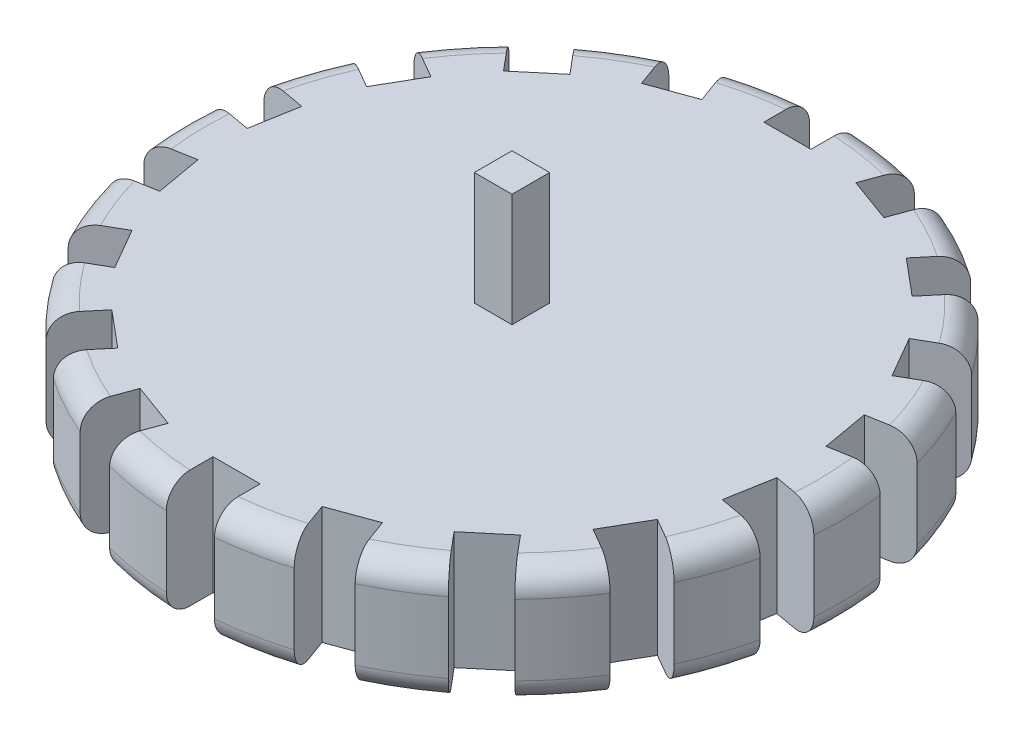
SolidWorks part; units mm, degrees
ref_plane "前视基准面" through (0, 0, 0) normal (0, 0, 1) x (1, 0, 0)
ref_plane "上视基准面" through (0, 0, 0) normal (0, 1, 0) x (1, 0, 0)
ref_plane "右视基准面" through (0, 0, 0) normal (1, 0, 0) x (0, 0, -1)
sketch "草图1" plane through (0, 0, 0) normal (0, 1, 0) x (1, 0, 0)
  line L1 (-27.9247, -7.2133) -> (-28.9247, -7.2133)
  line L2 (-27.9247, -7.2133) -> (-27.9247, -5.2133)
  line L3 (-27.9247, -5.2133) -> (-28.9247, -5.2133)
  line L4 (-28.9247, -7.2133) -> (-28.9247, -5.2133)
  circle A0 centre (-28.5698, 1.7867) radius 7
  dimension "D1" = 14
  dimension "D2" = 1
  dimension "D3" = 2
  dimension "D4" = 7
extrude "凸台-拉伸1" add sketch "草图1" along normal blind 2.5 contours A0
sketch "草图2" plane through (0, 2.5, 0) normal (0, 1, 0) x (1, 0, 0)
  line L1 (-28.9698, 2.1867) -> (-28.1698, 2.1867)
  line L2 (-28.9698, 2.1867) -> (-28.9698, 1.3867)
  line L3 (-28.9698, 1.3867) -> (-28.1698, 1.3867)
  line L4 (-28.1698, 2.1867) -> (-28.1698, 1.3867)
  line L5 (-28.9698, 2.1867) -> (-28.1698, 1.3867) construction
  line L6 (-28.9698, 1.3867) -> (-28.1698, 2.1867) construction
  point P0 (-28.5698, 1.7867)
extrude "凸台-拉伸2" add sketch "草图2" along normal blind 2.4
sketch "草图3" plane through (0, 0, 0) normal (0, -1, 0) x (1, 0, 0)
  circle A0 centre (-28.5698, -1.7867) radius 1
extrude "凸台-拉伸3" add sketch "草图3" along normal blind 1
fillet "圆角2" radius 0.5 2 edges at (-28.5698, 0, 5.2133) (-28.5698, 2.5, 5.2133)
sketch "草图4" plane through (0, 2.5, 0) normal (0, 1, 0) x (1, 0, 0)
  line L0 (-22.0698, 1.7867) -> (-35.0698, 1.7867) construction
  line L1 (-28.9177, -4.2133) -> (-27.9177, -4.2133)
  line L2 (-28.9177, -4.2133) -> (-28.9177, -6.2133)
  line L3 (-28.9177, -6.2133) -> (-27.9177, -6.2133)
  line L4 (-27.9177, -4.2133) -> (-27.9177, -6.2133)
  line L5 (-35.0698, 1.7867) -> (-28.5698, 8.2867) construction
  line L6 (-28.5698, 8.2867) -> (-28.5698, -4.7133) construction
  line L7 (-30.9489, -3.7325) -> (-31.6329, -5.6118)
  line L8 (-30.9489, -3.7325) -> (-30.0092, -4.0745)
  line L9 (-30.0092, -4.0745) -> (-30.6932, -5.9539)
  line L10 (-31.6329, -5.6118) -> (-30.6932, -5.9539)
  line L11 (-32.6931, -2.5859) -> (-33.9786, -4.118)
  line L12 (-32.6931, -2.5859) -> (-31.927, -3.2287)
  line L13 (-31.927, -3.2287) -> (-33.2126, -4.7608)
  line L14 (-33.9786, -4.118) -> (-33.2126, -4.7608)
  line L15 (-33.9399, -0.912) -> (-35.672, -1.912)
  line L16 (-33.9399, -0.912) -> (-33.4399, -1.778)
  line L17 (-33.4399, -1.778) -> (-35.172, -2.778)
  line L18 (-35.672, -1.912) -> (-35.172, -2.778)
  line L19 (-34.5391, 1.0874) -> (-36.5087, 0.7401)
  line L20 (-34.5391, 1.0874) -> (-34.3654, 0.1026)
  line L21 (-34.3654, 0.1026) -> (-36.3351, -0.2447)
  line L22 (-36.5087, 0.7401) -> (-36.3351, -0.2447)
  line L23 (-34.4183, 3.1712) -> (-36.3879, 3.5185)
  line L24 (-34.4183, 3.1712) -> (-34.5919, 2.1864)
  line L25 (-34.5919, 2.1864) -> (-36.5615, 2.5337)
  line L26 (-36.3879, 3.5185) -> (-36.5615, 2.5337)
  line L27 (-33.592, 5.088) -> (-35.3241, 6.088)
  line L28 (-33.592, 5.088) -> (-34.092, 4.222)
  line L29 (-34.092, 4.222) -> (-35.8241, 5.222)
  line L30 (-35.3241, 6.088) -> (-35.8241, 5.222)
  line L31 (-32.1601, 6.6066) -> (-33.4456, 8.1387)
  line L32 (-32.1601, 6.6066) -> (-32.9261, 5.9638)
  line L33 (-32.9261, 5.9638) -> (-34.2117, 7.4959)
  line L34 (-33.4456, 8.1387) -> (-34.2117, 7.4959)
  line L35 (-30.295, 7.5439) -> (-30.9791, 9.4232)
  line L36 (-30.295, 7.5439) -> (-31.2347, 7.2018)
  line L37 (-31.2347, 7.2018) -> (-31.9188, 9.0812)
  line L38 (-30.9791, 9.4232) -> (-31.9188, 9.0812)
  line L39 (-28.2219, 7.7867) -> (-28.2219, 9.7867)
  line L40 (-28.2219, 7.7867) -> (-29.2219, 7.7867)
  line L41 (-29.2219, 7.7867) -> (-29.2219, 9.7867)
  line L42 (-28.2219, 9.7867) -> (-29.2219, 9.7867)
  line L43 (-26.1908, 7.3059) -> (-25.5068, 9.1853)
  line L44 (-26.1908, 7.3059) -> (-27.1305, 7.6479)
  line L45 (-27.1305, 7.6479) -> (-26.4465, 9.5273)
  line L46 (-25.5068, 9.1853) -> (-26.4465, 9.5273)
  line L47 (-24.4466, 6.1594) -> (-23.161, 7.6915)
  line L48 (-24.4466, 6.1594) -> (-25.2127, 6.8022)
  line L49 (-25.2127, 6.8022) -> (-23.9271, 8.3342)
  line L50 (-23.161, 7.6915) -> (-23.9271, 8.3342)
  line L51 (-23.1997, 4.4854) -> (-21.4677, 5.4854)
  line L52 (-23.1997, 4.4854) -> (-23.6997, 5.3515)
  line L53 (-23.6997, 5.3515) -> (-21.9677, 6.3515)
  line L54 (-21.4677, 5.4854) -> (-21.9677, 6.3515)
  line L55 (-22.6006, 2.486) -> (-20.631, 2.8333)
  line L56 (-22.6006, 2.486) -> (-22.7742, 3.4708)
  line L57 (-22.7742, 3.4708) -> (-20.8046, 3.8181)
  line L58 (-20.631, 2.8333) -> (-20.8046, 3.8181)
  line L59 (-22.7214, 0.4022) -> (-20.7518, 0.0549)
  line L60 (-22.7214, 0.4022) -> (-22.5478, 1.387)
  line L61 (-22.5478, 1.387) -> (-20.5781, 1.0397)
  line L62 (-20.7518, 0.0549) -> (-20.5781, 1.0397)
  line L63 (-23.5476, -1.5146) -> (-21.8156, -2.5146)
  line L64 (-23.5476, -1.5146) -> (-23.0476, -0.6485)
  line L65 (-23.0476, -0.6485) -> (-21.3156, -1.6485)
  line L66 (-21.8156, -2.5146) -> (-21.3156, -1.6485)
  line L67 (-24.9796, -3.0332) -> (-23.694, -4.5653)
  line L68 (-24.9796, -3.0332) -> (-24.2136, -2.3904)
  line L69 (-24.2136, -2.3904) -> (-22.928, -3.9225)
  line L70 (-23.694, -4.5653) -> (-22.928, -3.9225)
  line L71 (-26.8446, -3.9704) -> (-26.1606, -5.8498)
  line L72 (-26.8446, -3.9704) -> (-25.9049, -3.6284)
  line L73 (-25.9049, -3.6284) -> (-25.2209, -5.5078)
  line L74 (-26.1606, -5.8498) -> (-25.2209, -5.5078)
  circle A0 centre (-28.5698, 1.7867) radius 6.5 construction
  point P13 (-28.4177, -4.2133)
  point P14 (-28.5698, 1.7867)
  point P83 (-28.5698, 1.7867)
  dimension "D1" = 2
  dimension "D2" = 1
  dimension "D3" = 6
  dimension "D4" = 18
extrude "切除-拉伸1" cut sketch "草图4" against normal blind 10
